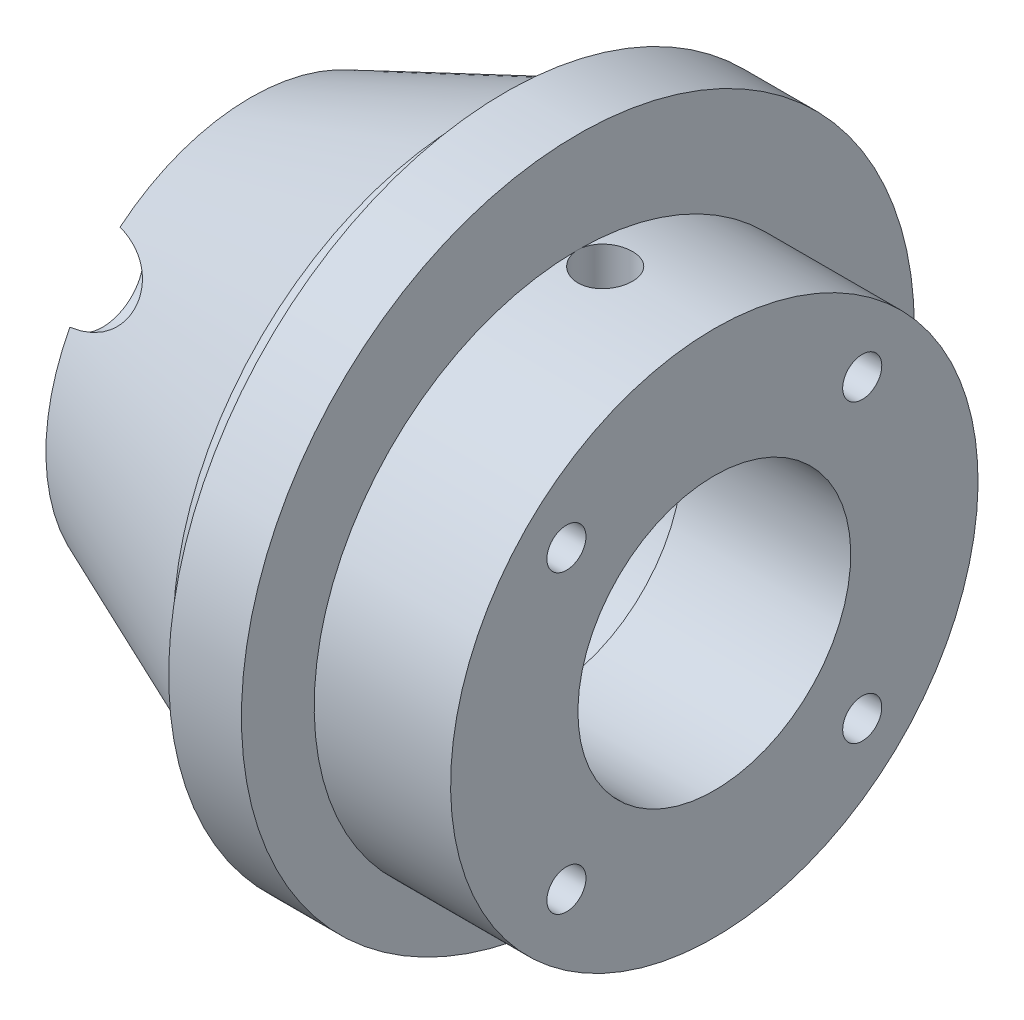
SolidWorks part; units mm, degrees
ref_plane "Face" through (0, 0, 0) normal (0, 0, 1) x (1, 0, 0)
ref_plane "Dessus" through (0, 0, 0) normal (0, 1, 0) x (1, 0, 0)
ref_plane "Droite" through (0, 0, 0) normal (1, 0, 0) x (0, 0, -1)
sketch "Esquisse2" plane through (0, 0, 0) normal (0, 0, 1) x (1, 0, 0)
  line L0 (0, 0) -> (0, 29)
  line L1 (0, 29) -> (-15, 29)
  line L2 (-15, 0) -> (-15, 29)
  line L3 (10, 0) -> (-20, 0) construction
  line L4 (-15, 0) -> (0, 0)
  dimension "D3" = 15
  dimension "D4" = 58
revolve "Base-Révolution" add sketch "Esquisse2" angle 360 about L3
sketch "Esquisse4" plane through (0, 0, 0) normal (0, 0, 1) x (1, 0, 0)
  line L0 (-51, 3) -> (-73.6764, 3) construction
  line L1 (-15, 3) -> (-15, 40)
  line L2 (-23, 35.5) -> (-27, 35.5)
  line L3 (-15, 40) -> (-23, 40)
  line L4 (-23, 40) -> (-23, 35.5)
  line L5 (-27, 35.5) -> (-51, 25.5)
  line L6 (-51, 25.5) -> (-51, 3)
  line L9 (-15, 3) -> (-51, 3)
  line L11 (-15, 0) -> (-15, 29) construction
  line L14 (10, 0) -> (-20, 0) construction
  dimension "D1" = 3
  dimension "D2" = 74
  dimension "D3" = 32.5
  dimension "D4" = 22.5
  dimension "D5" = 28
  dimension "D6" = 8
  dimension "D7" = 4
revolve "Boss.-Révol.1" add sketch "Esquisse4" angle 360 about L0
sketch "Esquisse6" plane through (-51, 0, 0) normal (-1, 0, 0) x (0, 0, 1)
  line L0 (0, 0) -> (0, 41.2311) construction
  line L1 (0, 0) -> (-28.3728, 28.3728) construction
  circle A0 centre (0, 0) radius 23 construction
  circle A2 centre (-16.2635, 16.2635) radius 4.5
  dimension "D1" = 9
  dimension "D2" = 45
  dimension "D3" = 46
extrude "Enlèv. mat.-Extru.1" cut sketch "Esquisse6" against normal blind 15
sketch "Esquisse7" plane through (-36, 0, 0) normal (-1, 0, 0) x (0, 0, 1)
  circle A0 centre (-16.2635, 16.2635) radius 2.15
  dimension "D1" = 4.3
extrude "Enlèv. mat.-Extru.2" cut sketch "Esquisse7" against normal through all
pattern_circular "Répétition circulaire1" count 4 every 90 about axis through (0, 0, 0) along (1, 0, 0) of "Enlèv. mat.-Extru.1", "Enlèv. mat.-Extru.2"
sketch "Esquisse13" plane through (0, 0, 0) normal (0, 0, 1) x (1, 0, 0)
  line L0 (3, 0) -> (3, 15)
  line L1 (-55, 0) -> (195, 0) construction
  line L2 (3, 15) -> (-18.5, 15)
  line L3 (-18.5, 15) -> (-18.5, 16)
  line L4 (-18.5, 16) -> (-51, 16)
  line L5 (-51, 25.5) -> (-51, 3) construction
  line L6 (-51, 16) -> (-51, 0)
  line L7 (-51, 0) -> (3, 0)
  line L8 (3, 6) -> (3, 0) construction
  line L9 (-31.7, 16) -> (-25.3, 16) construction
  line L11 (3, 0) -> (-62.1937, 0) construction
  line L12 (0, -29) -> (0, 29) construction
  dimension "D1" = 1
  dimension "D2" = 18.5
revolve "Enlèvement de matière-Révolution1" cut sketch "Esquisse13" angle 360 about L11
sketch "Esquisse14" plane through (0, 0, 0) normal (0, 0, 1) x (1, 0, 0)
  line L0 (-44.6643, 0) -> (-50.0344, 0) construction
  line L1 (-49.8, 16) -> (-48.4, 16)
  line L2 (-49.8, 16) -> (-49.8, 16.85)
  line L3 (-49.8, 16.85) -> (-48.4, 16.85)
  line L4 (-48.4, 16) -> (-48.4, 16.85)
  line L5 (-55, 0) -> (195, 0) construction
  line L6 (-48.2, 16) -> (-41.8, 16) construction
  line L7 (-48.5, 15.7) -> (-48.5, 10.3) construction
  dimension "D1" = 33.7
  dimension "D2" = 0.1
  dimension "D3" = 1.3
revolve "Enlèvement de matière-Révolution2" cut sketch "Esquisse14" angle 360 about L0
sketch "Esquisse15" plane through (0, 0, 0) normal (0, 1, 0) x (1, 0, 0)
  line L0 (-15, -29) -> (-15, 29) construction
  circle A0 centre (-12, 0) radius 3
  dimension "D1" = 6
  dimension "D2" = 3
extrude "Extrusion1" cut sketch "Esquisse15" along normal through all
